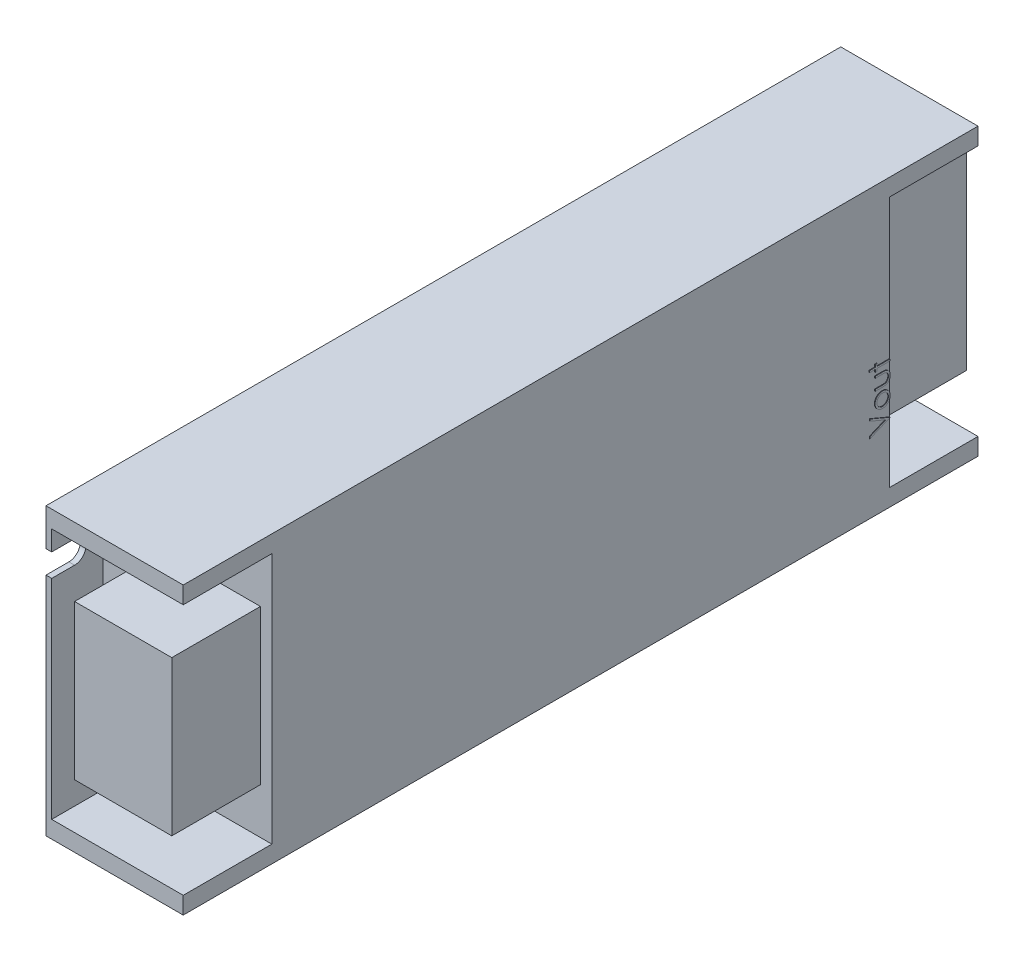
SolidWorks part; units mm, degrees
ref_plane "Front Plane" through (0, 0, 0) normal (0, 0, 1) x (1, 0, 0)
ref_plane "Top Plane" through (0, 0, 0) normal (0, 1, 0) x (1, 0, 0)
ref_plane "Right Plane" through (0, 0, 0) normal (1, 0, 0) x (0, 0, -1)
sketch "Skica1" plane through (0, 0, 0) normal (0, 0, 1) x (1, 0, 0)
  line L1 (0, 0) -> (24, 0)
  line L2 (0, 0) -> (0, 50)
  line L3 (0, 50) -> (24, 50)
  line L4 (24, 0) -> (24, 50)
  dimension "D1" = 24
  dimension "D2" = 50
extrude "Přidat vysunutím1" add sketch "Skica1" along normal blind 139
sketch "Skica2" plane through (24, 0, 0) normal (1, 0, 0) x (0, 0, -1)
  line L0 (-139, 25) -> (0, 25) construction
  line L1 (-139, 0) -> (-139, 50) construction
  line L2 (0, 0) -> (0, 50) construction
  line L3 (-69.5, 25) -> (-69.5, 41.9689) construction
  line L4 (-139, 50) -> (0, 50) construction
  line L5 (-123.5, 47) -> (-139, 47)
  line L6 (-123.5, 47) -> (-123.5, 3)
  line L7 (-123.5, 3) -> (-139, 3)
  line L8 (-139, 47) -> (-139, 3)
  line L9 (-123.5, 47) -> (-139, 3) construction
  line L10 (-123.5, 3) -> (-139, 47) construction
  line L11 (-15.5, 3) -> (0, 3)
  line L12 (0, 47) -> (0, 3)
  line L13 (-15.5, 47) -> (0, 47)
  line L14 (-15.5, 47) -> (-15.5, 3)
  point P8 (-131.25, 25)
  dimension "D1" = 3
  dimension "D2" = 15.5
extrude "Odebrat vysunutím1" cut sketch "Skica2" against normal offset from surface (19 mm away) 5 up to face at (0, 25, 69.5)
sketch "Skica4" plane through (5, 0, 0) normal (1, 0, 0) x (0, 0, -1)
  line L0 (-139, 47) -> (-123.5, 47) construction
  line L1 (-130, 47) -> (-139, 47)
  line L2 (-130, 47) -> (-130, 3)
  line L3 (-130, 3) -> (-139, 3)
  line L4 (-139, 47) -> (-139, 3)
  line L10 (0, 47) -> (-15.5, 47) construction
  line L11 (-9, 47) -> (0, 47)
  line L12 (-9, 47) -> (-9, 3)
  line L13 (-9, 3) -> (0, 3)
  line L14 (0, 47) -> (0, 3)
  dimension "D1" = 9
  dimension "D2" = 9
extrude "Odebrat vysunutím2" cut sketch "Skica4" against normal offset from surface (4 mm away) 1 up to face at (0, 25, 69.5)
sketch "Skica5" plane through (5, 0, 0) normal (1, 0, 0) x (0, 0, -1)
  line L0 (-123.5, 47) -> (-123.5, 3) construction
  line L1 (-123.5, 38) -> (-139, 38)
  line L2 (-123.5, 38) -> (-123.5, 11)
  line L3 (-123.5, 11) -> (-139, 11)
  line L4 (-139, 38) -> (-139, 11)
  line L5 (-139, 3) -> (-139, 47) construction
  line L6 (-15.5, 47) -> (-15.5, 3) construction
  line L7 (-15.5, 12) -> (0, 12)
  line L8 (-15.5, 12) -> (-15.5, 47)
  line L9 (-15.5, 47) -> (0, 47)
  line L10 (0, 12) -> (0, 47)
  line L11 (-139, 47) -> (-130, 47) construction
  point P17 (-134.5, 47)
  dimension "D1" = 27
  dimension "D2" = 35
  dimension "D3" = 9
extrude "Přidat vysunutím2" add sketch "Skica5" along normal offset from surface (17 mm away) 2 up to face at (24, 25, 69.5)
sketch "Skica6" plane through (24, 0, 0) normal (1, 0, 0) x (0, 0, -1)
  line L0 (-23.3471, 50) -> (-23.3471, 0) construction
  line L1 (-139, 50) -> (0, 50) construction
  line L2 (-139, 0) -> (0, 0) construction
  text T0 "Vout"
extrude "Přidat vysunutím3" add sketch "Skica6" along normal blind 0.1
sketch "Skica7" plane through (1, 0, 0) normal (1, 0, 0) x (0, 0, -1)
  line L0 (-139, 41.5) -> (-135, 41.5) construction
  line L1 (-139, 3) -> (-139, 47) construction
  line L2 (-139, 43.5) -> (-135, 43.5)
  line L3 (-139, 39.5) -> (-135, 39.5)
  line L4 (0, 8.5) -> (-4, 8.5) construction
  line L5 (0, 47) -> (0, 3) construction
  line L6 (0, 6.5) -> (-4, 6.5)
  line L7 (0, 10.5) -> (-4, 10.5)
  line L8 (-139, 50) -> (0, 50) construction
  line L9 (-139, 0) -> (0, 0) construction
  arc A0 (-139, 43.5) -> (-139, 39.5) centre (-139, 41.5) ccw
  arc A1 (-135, 39.5) -> (-135, 43.5) centre (-135, 41.5) ccw
  arc A2 (0, 6.5) -> (0, 10.5) centre (0, 8.5) ccw
  arc A3 (-4, 10.5) -> (-4, 6.5) centre (-4, 8.5) ccw
  point P4 (-137, 41.5)
  point P9 (-2, 8.5)
  dimension "D1" = 2
  dimension "D2" = 2
  dimension "D3" = 4
  dimension "D4" = 4
  dimension "D5" = 6.5
  dimension "D6" = 6.5
extrude "Odebrat vysunutím3" cut sketch "Skica7" against normal blind 10
